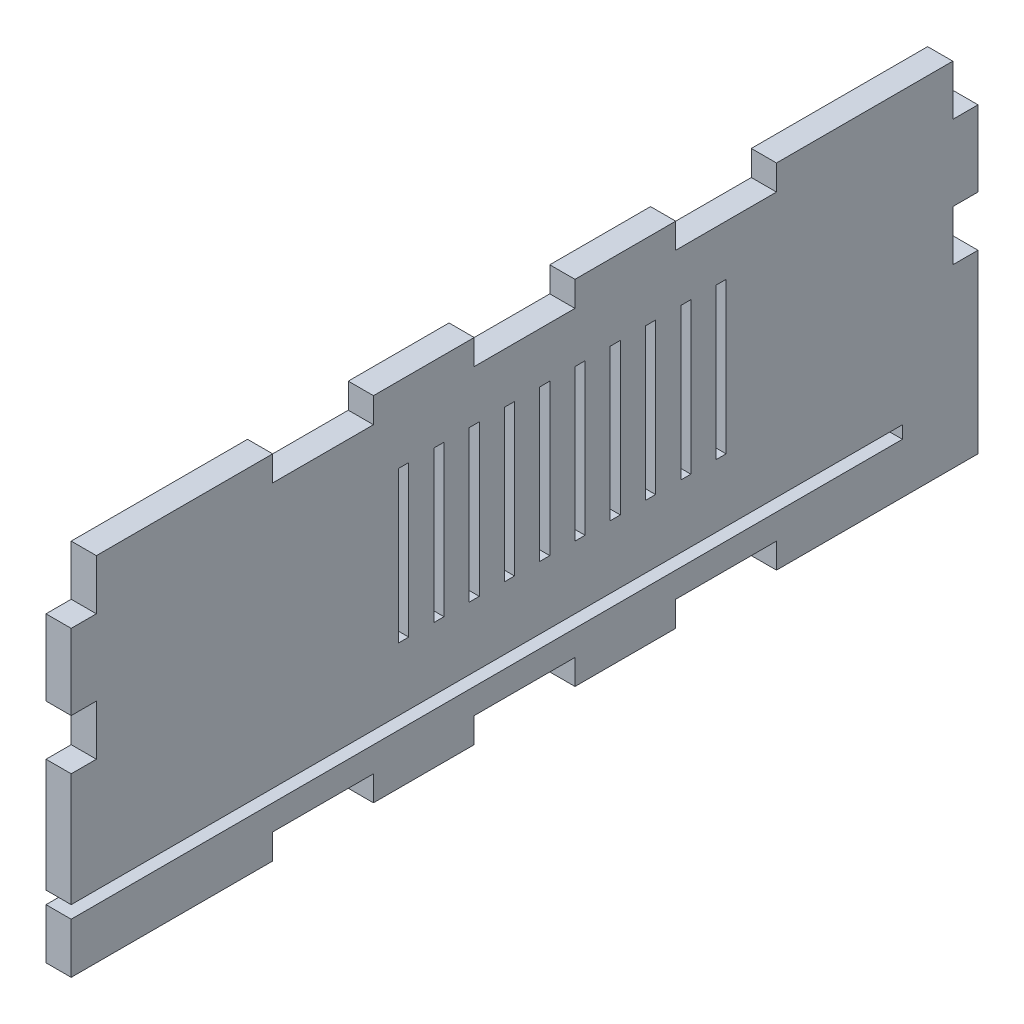
SolidWorks part; units mm, degrees
ref_plane "Plan de face" through (0, 0, 0) normal (0, 0, 1) x (1, 0, 0)
ref_plane "Plan de dessus" through (0, 0, 0) normal (0, 1, 0) x (1, 0, 0)
ref_plane "Plan de droite" through (0, 0, 0) normal (1, 0, 0) x (0, 0, -1)
sketch "Esquisse1" plane through (0, 0, 0) normal (1, 0, 0) x (0, 0, -1)
  line L1 (-90, 35) -> (90, 35)
  line L2 (-90, 35) -> (-90, -35)
  line L3 (-90, -35) -> (90, -35)
  line L4 (90, 35) -> (90, -35)
  line L5 (-90, 35) -> (90, -35) construction
  line L6 (-90, -35) -> (90, 35) construction
  point P0 (0, 0)
  dimension "D1" = 70
  dimension "D2" = 180
extrude "Boss.-Extru.1" add sketch "Esquisse1" along normal blind 5
sketch "Esquisse2" plane through (5, 0, 0) normal (1, 0, 0) x (0, 0, -1)
  line L0 (-90, -35) -> (90, -35) construction
  line L1 (-90, -22.5) -> (75, -22.5)
  line L2 (-90, -22.5) -> (-90, -25)
  line L3 (-90, -25) -> (75, -25)
  line L4 (75, -22.5) -> (75, -25)
  line L5 (-90, 35) -> (-90, -35) construction
  dimension "D1" = 2.5
  dimension "D2" = 165
  dimension "D3" = 10
extrude "Enlèv. mat.-Extru.1" cut sketch "Esquisse2" against normal blind 5
sketch "Esquisse3" plane through (5, 0, 0) normal (1, 0, 0) x (0, 0, -1)
  line L0 (-90, 35) -> (-90, -22.5) construction
  line L1 (-90, 35) -> (-85, 35)
  line L2 (-90, 35) -> (-90, 25)
  line L3 (-90, 25) -> (-85, 25)
  line L4 (-85, 35) -> (-85, 25)
  line L5 (-90, 10) -> (-85, 10)
  line L6 (-90, 10) -> (-90, 0)
  line L7 (-90, 0) -> (-85, 0)
  line L8 (-85, 10) -> (-85, 0)
  line L9 (90, -35) -> (90, 35) construction
  line L10 (90, 35) -> (85, 35)
  line L11 (90, 35) -> (90, 25)
  line L12 (90, 25) -> (85, 25)
  line L13 (85, 35) -> (85, 25)
  line L14 (90, 0) -> (85, 0)
  line L15 (90, 0) -> (90, 10)
  line L16 (90, 10) -> (85, 10)
  line L17 (85, 0) -> (85, 10)
  line L18 (90, 35) -> (-90, 35) construction
  line L19 (-50, 35) -> (-30, 35)
  line L20 (-50, 35) -> (-50, 30)
  line L21 (-50, 30) -> (-30, 30)
  line L22 (-30, 35) -> (-30, 30)
  line L24 (30, 35) -> (50, 35)
  line L25 (30, 35) -> (30, 30)
  line L26 (30, 30) -> (50, 30)
  line L27 (50, 35) -> (50, 30)
  line L28 (-10, 35) -> (10, 35)
  line L29 (-10, 35) -> (-10, 30)
  line L30 (-10, 30) -> (10, 30)
  line L31 (10, 35) -> (10, 30)
  line L32 (-90, -35) -> (90, -35) construction
  line L33 (-50, -35) -> (-30, -35)
  line L34 (-50, -35) -> (-50, -30)
  line L35 (-50, -30) -> (-30, -30)
  line L36 (-30, -35) -> (-30, -30)
  line L38 (-10, -35) -> (10, -35)
  line L39 (-10, -35) -> (-10, -30)
  line L40 (-10, -30) -> (10, -30)
  line L41 (10, -35) -> (10, -30)
  line L42 (30, -35) -> (50, -35)
  line L43 (30, -35) -> (30, -30)
  line L44 (30, -30) -> (50, -30)
  line L45 (50, -35) -> (50, -30)
  point P37 (0, 30)
  dimension "D1" = 5
  dimension "D2" = 10
  dimension "D3" = 5
  dimension "D4" = 10
  dimension "D5" = 15
  dimension "D6" = 10
  dimension "D7" = 5
  dimension "D8" = 5
  dimension "D9" = 10
  dimension "D10" = 15
  dimension "D11" = 5
  dimension "D12" = 20
  dimension "D13" = 20
  dimension "D14" = 20
  dimension "D15" = 20
  dimension "D16" = 20
  dimension "D17" = 5
extrude "Enlèv. mat.-Extru.2" cut sketch "Esquisse3" against normal blind 5
sketch "Esquisse4" plane through (5, 0, 0) normal (1, 0, 0) x (0, 0, -1)
  line L0 (31, 20) -> (31, -10)
  line L1 (38, 20) -> (40, 20)
  line L2 (38, 20) -> (38, -10)
  line L3 (38, -10) -> (40, -10)
  line L4 (40, 20) -> (40, -10)
  line L5 (31, 20) -> (33, 20)
  line L6 (33, 20) -> (33, -10)
  line L7 (31, -10) -> (33, -10)
  line L8 (24, 20) -> (24, -10)
  line L9 (24, 20) -> (26, 20)
  line L10 (26, 20) -> (26, -10)
  line L11 (24, -10) -> (26, -10)
  line L12 (17, 20) -> (17, -10)
  line L13 (17, 20) -> (19, 20)
  line L14 (19, 20) -> (19, -10)
  line L15 (17, -10) -> (19, -10)
  line L16 (10, 20) -> (10, -10)
  line L17 (10, 20) -> (12, 20)
  line L18 (12, 20) -> (12, -10)
  line L19 (10, -10) -> (12, -10)
  line L20 (3, 20) -> (3, -10)
  line L21 (3, 20) -> (5, 20)
  line L22 (5, 20) -> (5, -10)
  line L23 (3, -10) -> (5, -10)
  line L24 (-4, 20) -> (-4, -10)
  line L25 (-4, 20) -> (-2, 20)
  line L26 (-2, 20) -> (-2, -10)
  line L27 (-4, -10) -> (-2, -10)
  line L28 (-11, 20) -> (-11, -10)
  line L29 (-11, 20) -> (-9, 20)
  line L30 (-9, 20) -> (-9, -10)
  line L31 (-11, -10) -> (-9, -10)
  line L32 (-18, 20) -> (-18, -10)
  line L33 (-18, 20) -> (-16, 20)
  line L34 (-16, 20) -> (-16, -10)
  line L35 (-18, -10) -> (-16, -10)
  line L36 (-25, 20) -> (-25, -10)
  line L37 (-25, 20) -> (-23, 20)
  line L38 (-23, 20) -> (-23, -10)
  line L39 (-25, -10) -> (-23, -10)
  line L40 (90, -35) -> (90, 0) construction
  line L41 (-10, 30) -> (10, 30) construction
  point P44 (-72.6482, -10)
  dimension "D1" = 2
  dimension "D2" = 30
  dimension "D4" = 50
  dimension "D5" = 10
  dimension "D6" = 5
  dimension "D3" = 10
extrude "Enlèv. mat.-Extru.3" cut sketch "Esquisse4" against normal blind 5
